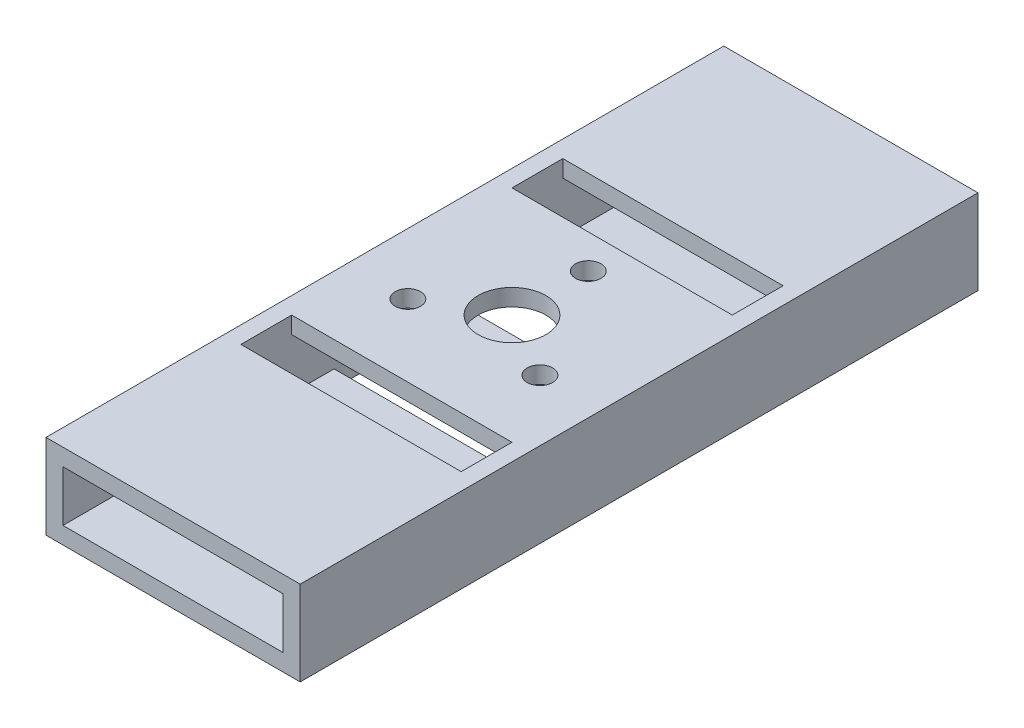
SolidWorks part; units mm, degrees
other "Marcação1"
sketch "Esboço11" plane through (15, 5, 80) normal (0.2715, 0.9623, 0.0173) x (0.947, -0.264, -0.1831)
ref_plane "Plano frontal" through (0, 0, 0) normal (0, 0, 1) x (1, 0, 0)
ref_plane "Plano superior" through (0, 0, 0) normal (0, 1, 0) x (1, 0, 0)
ref_plane "Plano direito" through (0, 0, 0) normal (1, 0, 0) x (0, 0, -1)
sketch "Esboço1" plane through (0, 0, 0) normal (0, 0, 1) x (1, 0, 0)
  line L5 (-15, -5) -> (15, -5)
  line L6 (-15, -5) -> (-15, 5)
  line L11 (-15, 5) -> (15, 5)
  line L12 (15, -5) -> (15, 5)
  line L15 (-13, 3) -> (13, 3)
  line L16 (-13, 3) -> (-13, -3)
  line L17 (-13, -3) -> (13, -3)
  line L18 (13, 3) -> (13, -3)
  point P0 (0, 0)
  point P6 (0, 0)
  dimension "D1" = 30
  dimension "D2" = 10
  dimension "D3" = 26
  dimension "D4" = 6
extrude "Ressalto-extrusão1" add sketch "Esboço1" along normal blind 80
sketch "Esboço2" plane through (0, 5, 0) normal (0, 1, 0) x (1, 0, 0)
  circle A0 centre (0, -40) radius 4
extrude "Corte-extrusão1" cut sketch "Esboço2" against normal blind 10
sketch "Esboço4" plane through (0, 5, 0) normal (0, 1, 0) x (1, 0, 0)
  circle A0 centre (0, -31) radius 1.5
  circle A1 centre (0, -40) radius 4 construction
  circle A2 centre (7.7942, -44.5) radius 1.5
  circle A3 centre (-7.7942, -44.5) radius 1.5
  point P10 (0, -40)
  dimension "D1" = 9
  dimension "D2" = 3
  dimension "D3" = 3
extrude "Corte-extrusão2" cut sketch "Esboço4" against normal blind 2
sketch "Esboço6" plane through (0, -5, 0) normal (0, -1, 0) x (-1, 0, 0)
  circle A0 centre (0, -56) radius 2
  circle A1 centre (0, -40) radius 4 construction
  dimension "D1" = 16
extrude "Corte-extrusão4" cut sketch "Esboço6" against normal blind 2
ref_plane "Plano1" through (0, 0, 40) normal (0, 0, 1) x (1, 0, 0)
mirror "Espelhar1" about plane through (0, 0, 40) normal (0, 0, 1) of "Corte-extrusão4"
sketch "Esboço7" plane through (0, 5, 0) normal (0, 1, 0) x (1, 0, 0)
  line L1 (-13, -21) -> (13, -21)
  line L2 (-13, -21) -> (-13, -27)
  line L3 (-13, -27) -> (13, -27)
  line L4 (13, -21) -> (13, -27)
  line L5 (-13, -21) -> (13, -27) construction
  line L6 (-13, -27) -> (13, -21) construction
  circle A0 centre (0, -40) radius 4 construction
  point P0 (0, -24)
  dimension "D1" = 16
  dimension "D2" = 6
  dimension "D3" = 26
extrude "Corte-extrusão5" cut sketch "Esboço7" against normal blind 2
mirror "Espelhar2" about plane through (0, 0, 40) normal (0, 0, 1) of "Corte-extrusão5"
sketch "Esboço8" plane through (0, -5, 0) normal (0, -1, 0) x (-1, 0, 0)
  line L1 (13, -34) -> (-13, -34)
  line L2 (13, -34) -> (13, -28)
  line L3 (13, -28) -> (-13, -28)
  line L4 (-13, -34) -> (-13, -28)
  line L5 (13, -34) -> (-13, -28) construction
  line L6 (13, -28) -> (-13, -34) construction
  circle A0 centre (0, -40) radius 4 construction
  point P0 (0, -31)
  dimension "D1" = 9
  dimension "D2" = 6
  dimension "D3" = 26
extrude "Corte-extrusão6" cut sketch "Esboço8" against normal blind 2
sketch "Esboço9" plane through (0, -5, 0) normal (0, -1, 0) x (-1, 0, 0)
sketch "Esboço10" plane through (0, -5, 0) normal (0, -1, 0) x (-1, 0, 0)
  line L1 (13, -40) -> (-13, -40)
  line L2 (13, -40) -> (13, -48)
  line L3 (13, -48) -> (-13, -48)
  line L4 (-13, -40) -> (-13, -48)
  line L5 (13, -40) -> (-13, -48) construction
  line L6 (13, -48) -> (-13, -40) construction
  circle A0 centre (0, -40) radius 4 construction
  point P0 (0, -44)
  dimension "D1" = 26
  dimension "D2" = 8
extrude "Corte-extrusão7" cut sketch "Esboço10" against normal blind 2
